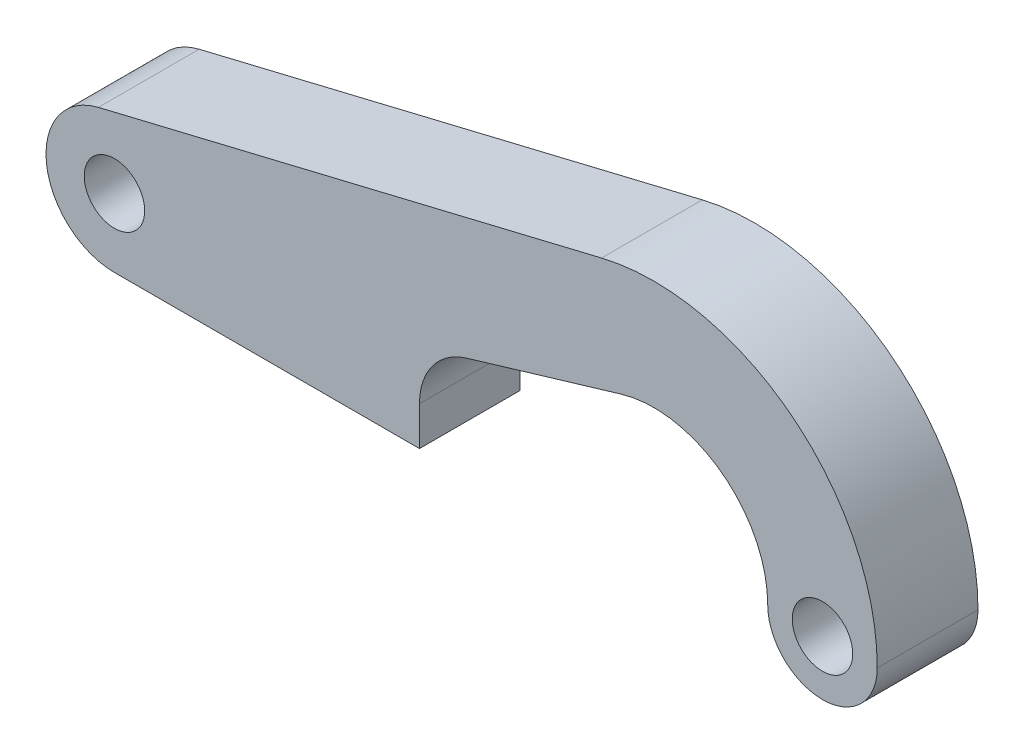
SolidWorks part; units mm, degrees
ref_plane "Front Plane" through (0, 0, 0) normal (0, 0, 1) x (1, 0, 0)
ref_plane "Top Plane" through (0, 0, 0) normal (0, 1, 0) x (1, 0, 0)
ref_plane "Right Plane" through (0, 0, 0) normal (1, 0, 0) x (0, 0, -1)
sketch "Sketch2" plane through (0, 0, 2.794) normal (0, 0, 1) x (1, 0, 0)
  line L0 (31.2738, 0.8255) -> (41.0527, 0.8255) construction
  line L1 (-0.9287, 6.3986) -> (28.2424, 13.4198)
  line L2 (0, -1.4287) -> (24.6698, -1.4287)
  line L3 (24.6698, -1.4287) -> (24.6698, 0.8255)
  circle A0 centre (31.2738, 0.8255) radius 6.35 construction
  circle A1 centre (31.2738, 0.8255) radius 6.35 construction
  circle A3 centre (0, 2.54) radius 1.7526
  arc A4 (28.2424, 13.4198) -> (44.2278, 0.8255) centre (31.2738, 0.8255) cw
  arc A5 (-0.9287, 6.3986) -> (0, -1.4287) centre (0, 2.54) ccw
  arc A6 (24.6698, 0.8255) -> (37.8777, 0.8255) centre (31.2738, 0.8255) cw
  arc A7 (37.8777, 0.8255) -> (44.2278, 0.8255) centre (41.0527, 0.8255) ccw
  circle A8 centre (41.0527, 0.8255) radius 1.7526
  circle A10 centre (0, 2.54) radius 3.9687 construction
  circle A11 centre (31.2738, 0.8255) radius 6.35 construction
  dimension "D1" = 9.779
  dimension "D2" = 3.5052
  dimension "D4" = 3.5052
  dimension "D3" = 6.35
extrude "Boss-Extrude1" add sketch "Sketch2" along normal blind 5.842
sketch "Sketch3" plane through (0, 0, 8.636) normal (0, 0, 1) x (1, 0, 0)
  line L0 (37.8777, -10.0527) -> (37.8777, 0.8255)
  line L2 (17.6847, 0.8255) -> (17.6847, -10.0527)
  line L3 (17.6847, -10.0527) -> (37.8777, -10.0527)
  line L4 (20.4062, 4.4767) -> (29.3869, 7.1542)
  arc A2 (24.6698, 0.8255) -> (18.3197, 0.8255) centre (21.4948, 0.8255) ccw construction
  arc A4 (37.8777, 0.8255) -> (24.6698, 0.8255) centre (31.2738, 0.8255) ccw construction
  arc A5 (37.8777, 0.8255) -> (29.3869, 7.1542) centre (31.2738, 0.8255) ccw
  arc A6 (20.4062, 4.4767) -> (17.6847, 0.8255) centre (21.4948, 0.8255) ccw
  dimension "D1" = 0.635
  dimension "D2" = 10.8782
extrude "Cut-Extrude1" cut sketch "Sketch3" against normal through all
